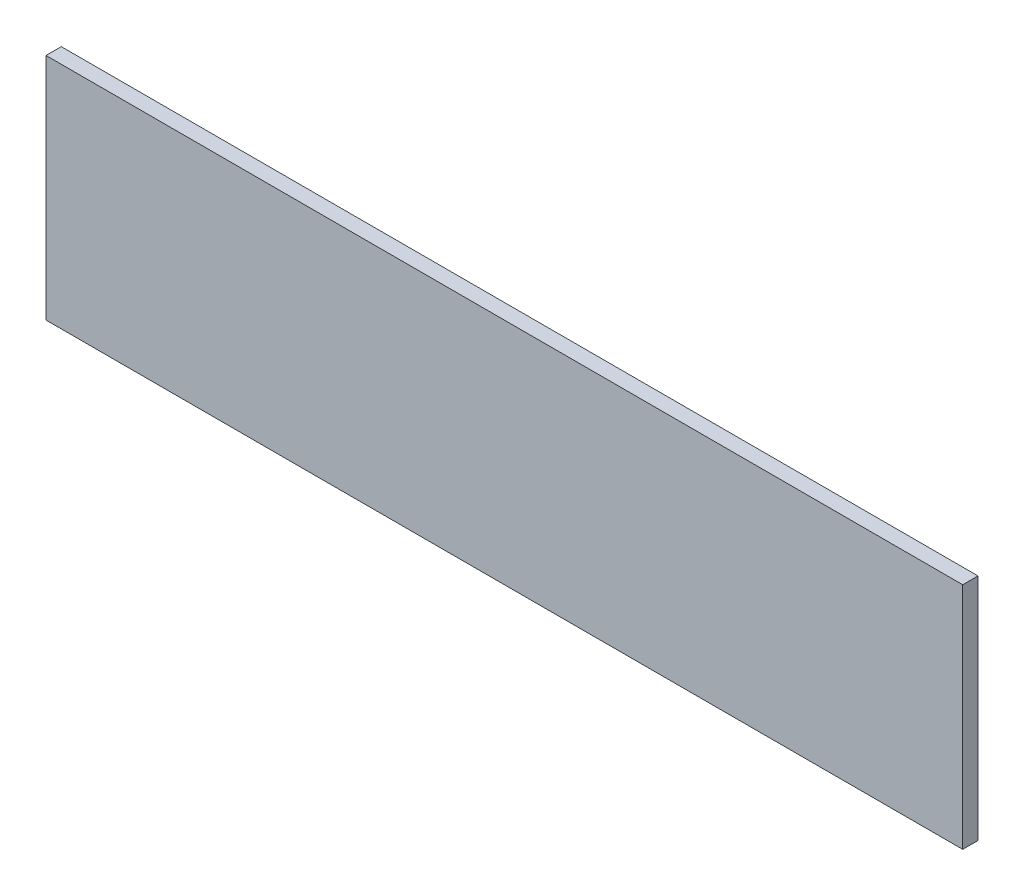
SolidWorks part; units mm, degrees
ref_plane "Piano frontale" through (0, 0, 0) normal (0, 0, 1) x (1, 0, 0)
ref_plane "Piano superiore" through (0, 0, 0) normal (0, 1, 0) x (1, 0, 0)
ref_plane "Piano destro" through (0, 0, 0) normal (1, 0, 0) x (0, 0, -1)
sketch "Schizzo1" plane through (0, 0, 0) normal (0, 0, 1) x (1, 0, 0)
  line L1 (0, 0) -> (120, 0)
  line L2 (0, 0) -> (0, 30)
  line L3 (0, 30) -> (120, 30)
  line L4 (120, 0) -> (120, 30)
  dimension "D1" = 30
  dimension "D2" = 120
extrude "Estrusione-Estrusione1" add sketch "Schizzo1" along normal blind 2
